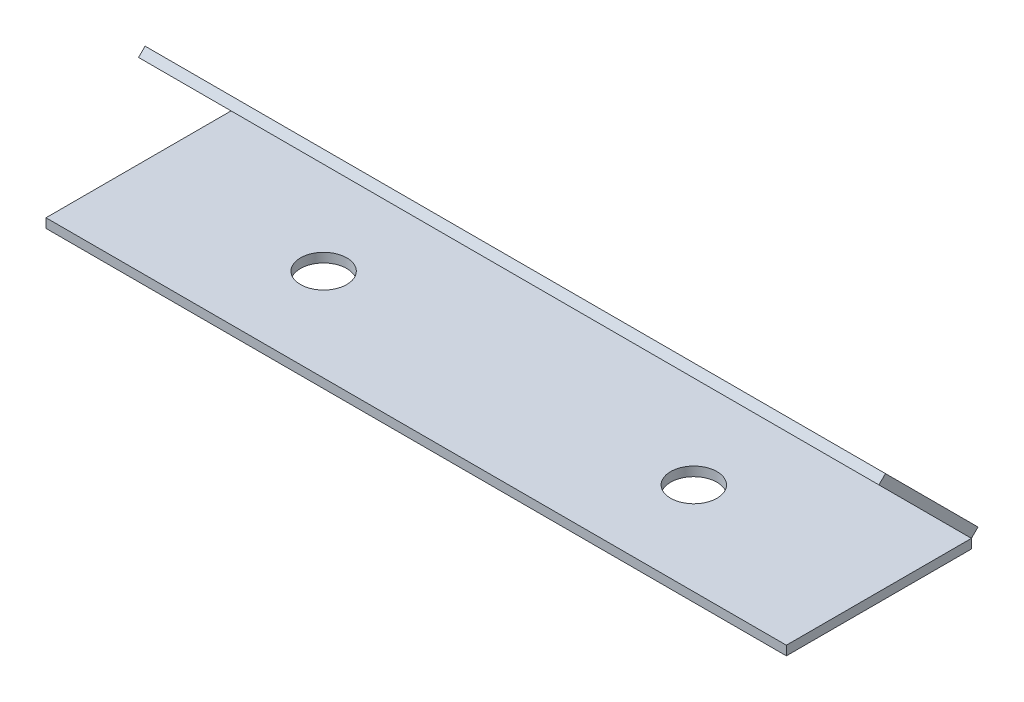
SolidWorks part; units mm, degrees
ref_plane "Front Plane" through (0, 0, 0) normal (0, 0, 1) x (1, 0, 0)
ref_plane "Top Plane" through (0, 0, 0) normal (0, 1, 0) x (1, 0, 0)
ref_plane "Right Plane" through (0, 0, 0) normal (1, 0, 0) x (0, 0, -1)
sketch "Sketch2" plane through (0, 0, 0) normal (0, 1, 0) x (1, 0, 0)
  line L1 (-10, 2.5) -> (10, 2.5)
  line L2 (-10, 2.5) -> (-10, -2.5)
  line L3 (-10, -2.5) -> (10, -2.5)
  line L4 (10, 2.5) -> (10, -2.5)
  line L5 (-10, 2.5) -> (10, -2.5) construction
  line L6 (-10, -2.5) -> (10, 2.5) construction
  circle A0 centre (-5, 0) radius 0.625
  circle A1 centre (5, 0) radius 0.625
  point P0 (0, 0)
  point P10 (0, 0)
  point P11 (0, 0)
  dimension "D3" = 1.25
  dimension "D4" = 1.25
  dimension "D7" = 2.5
  dimension "D1" = 20
  dimension "D2" = 5
  dimension "D5" = 5
  dimension "D6" = 5
  dimension "D8" = 2.5
extrude "Boss-Extrude1" add sketch "Sketch2" along normal blind 0.25
ref_plane "Plane1" through (0, 1.375, -1.375) normal (0, 0.7071, -0.7071) x (-1, 0, 0)
sketch "Sketch5" plane through (0, 1.375, -1.375) normal (0, 0.7071, -0.7071) x (-1, 0, 0)
  line L0 (-10, -1.591) -> (10, -1.591)
  line L1 (10, -1.591) -> (10, 1.9445)
  line L2 (10, 1.9445) -> (-10, 1.9445) construction
  line L3 (10, -1.591) -> (10, 1.9445) construction
  line L4 (10, 1.9445) -> (-10, 1.9445)
  line L5 (-10, 1.9445) -> (-10, -1.591)
  circle A0 centre (-4.9887, 0) radius 0.625
  circle A1 centre (5.0113, 0) radius 0.625
  dimension "D1" = 1.25
  dimension "D2" = 1.25
  dimension "D3" = 10
extrude "Boss-Extrude5" add sketch "Sketch5" along normal blind 0.25 separate body
